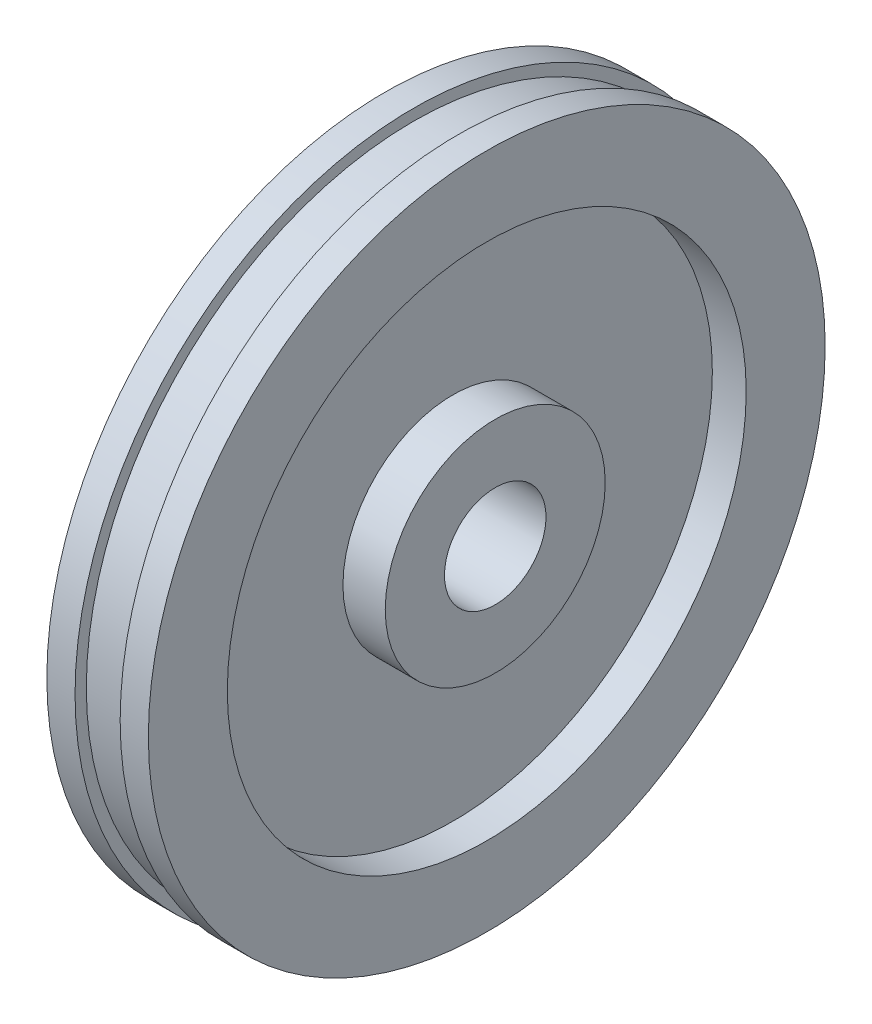
SolidWorks part; units mm, degrees
ref_plane "Plan de face" through (0, 0, 0) normal (0, 0, 1) x (1, 0, 0)
ref_plane "Plan de dessus" through (0, 0, 0) normal (0, 1, 0) x (1, 0, 0)
ref_plane "Plan de droite" through (0, 0, 0) normal (1, 0, 0) x (0, 0, -1)
sketch "Esquisse1" plane through (0, 0, 0) normal (0, 0, 1) x (1, 0, 0)
  line L0 (0, 0) -> (21, 0)
  line L1 (21, 0) -> (21, 10.5)
  line L2 (21, 10.5) -> (13.5, 10.5)
  line L3 (13.5, 10.5) -> (13.5, 37)
  line L4 (13.5, 37) -> (19.5, 37)
  line L5 (19.5, 37) -> (19.5, 51)
  line L6 (19.5, 51) -> (14.5, 51)
  line L7 (14.5, 51) -> (14.5, 49)
  line L8 (14.5, 49) -> (6.5, 49)
  line L9 (6.5, 49) -> (6.5, 51)
  line L10 (6.5, 51) -> (1.5, 51)
  line L11 (1.5, 51) -> (1.5, 37)
  line L12 (1.5, 37) -> (7.5, 37)
  line L13 (7.5, 37) -> (7.5, 10.5)
  line L14 (7.5, 10.5) -> (0, 10.5)
  line L15 (0, 10.5) -> (0, 0)
  line L16 (10.5, 0) -> (10.5, 49) construction
  line L17 (0, -9) -> (21, -9) construction
  point P21 (10.5, 49)
  point P22 (10.5, 49)
  dimension "D1" = 21
  dimension "D2" = 18
  dimension "D3" = 39
  dimension "D4" = 8
  dimension "D5" = 120
  dimension "D6" = 6
  dimension "D7" = 14
  dimension "D8" = 2
  dimension "D9" = 18
revolve "Révolution1" add sketch "Esquisse1" angle 360 about L17
